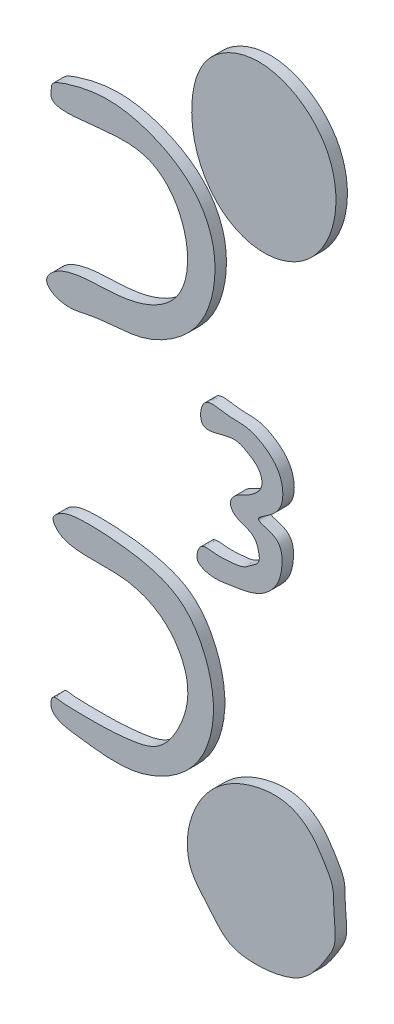
SolidWorks part; units mm, degrees
ref_plane "Plan de face" through (0, 0, 0) normal (0, 0, 1) x (1, 0, 0)
ref_plane "Plan de dessus" through (0, 0, 0) normal (0, 1, 0) x (1, 0, 0)
ref_plane "Plan de droite" through (0, 0, 0) normal (1, 0, 0) x (0, 0, -1)
sketch "Esquisse2" plane through (0, 0, 0) normal (0, 0, 1) x (1, 0, 0)
  spline S0 degree 3 poles (33.0398, 33.3108) (30.8437, 35.5747) (31.1487, 39.7884) (33.649, 43.2304) (37.0758, 44.68) (40.0093, 44.8048) (41.9924, 43.4542) (42.9933, 41.8752) (43.998, 40.2637) (43.802, 38.1648) (44.2434, 36.1904) (43.2504, 34.5258) (42.3581, 33.1589) (41.0307, 31.8624) (39.0658, 31.1858) (37.0142, 30.9623) (34.507, 31.3137) (33.0398, 33.3108) (30.8437, 35.5747) (31.1487, 39.7884) knots -0.170245 -0.123255 -0.059426 0 0.100099 0.211398 0.293708 0.362648 0.413623 0.458262 0.498625 0.546325 0.607041 0.636395 0.682371 0.726525 0.767054 0.829755 0.876745 0.940574 1 1.100099 1.211398 1.293708 only from (31.4862, 35.2825) to (31.4862, 35.2825)
  spline S1 degree 3 poles (32.2441, 97.9616) (31.205, 93.273) (31.9073, 89.3567) (33.8805, 86.3625) (37.3836, 84.8702) (41.5831, 85.9325) (44.5304, 90.388) (43.9096, 96.8861) (37.9571, 100.5086) (32.2441, 97.9616) (31.205, 93.273) (31.9073, 89.3567) knots -0.396579 -0.237542 -0.122038 0 0.076955 0.165433 0.247247 0.336953 0.456005 0.603421 0.762458 0.877962 1 1.076955 1.165433 1.247247 only from (31.4862, 92.6971) to (31.4862, 92.6971)
  spline S2 degree 3 poles (33.0432, 58.3081) (31.9134, 59.0241) (31.9311, 59.7097) (32.351, 60.568) (33.6185, 60.2941) (34.7915, 60.3881) (36.0182, 60.4842) (36.7184, 61.0966) (37.4833, 61.5586) (37.3384, 62.4873) (37.0146, 63.4183) (35.9976, 63.7876) (35.1127, 64.1142) (34.738, 64.9543) (35.2839, 65.7476) (36.153, 66.0752) (37.0241, 66.6082) (37.8092, 67.4844) (37.4074, 68.808) (36.3921, 69.4215) (34.8527, 70.2582) (31.986, 68.4617) (32.3579, 71.9659) (34.5883, 71.2479) (36.2703, 71.4438) (37.9414, 70.6474) (39.3618, 69.3261) (39.6137, 67.0468) (38.6303, 65.7785) (36.6531, 64.6995) (39.3775, 64.4209) (39.458, 62.4037) (39.0449, 60.6182) (37.4986, 59.0304) (35.0525, 58.6733) (33.0432, 58.3081) (31.9134, 59.0241) (31.9311, 59.7097) knots -0.116764 -0.062902 -0.006445 0 0.015981 0.029747 0.053635 0.082119 0.107798 0.124873 0.139963 0.15785 0.175957 0.198943 0.220104 0.23258 0.249661 0.271846 0.289785 0.313456 0.33757 0.363431 0.385064 0.446145 0.480391 0.519875 0.557582 0.58962 0.62952 0.67429 0.712535 0.736788 0.767963 0.811468 0.841391 0.883236 0.937098 0.993555 1 1.015981 1.029747 1.053635 only from (32.0774, 58.9558) to (32.0774, 58.9558)
  spline S3 degree 3 poles (22.9392, 40.3254) (18.9015, 40.9013) (19.2856, 42.5705) (20.2561, 42.3662) (21.6214, 42.3661) (23.6576, 42.3235) (25.9895, 42.4952) (28.6733, 42.9232) (30.5952, 45.6426) (31.6672, 49.4038) (29.5627, 53.2139) (25.5262, 54.8588) (22.2823, 54.3367) (19.9422, 54.8913) (19.116, 55.9998) (20.2334, 56.887) (22.0843, 57.1421) (24.7434, 56.9976) (27.7768, 56.5987) (30.8976, 55.3873) (33.0573, 51.9513) (33.7675, 47.4671) (31.8201, 42.6417) (26.7961, 39.8912) (22.9392, 40.3254) (18.9015, 40.9013) (19.2856, 42.5705) knots -0.191879 -0.116365 -0.037915 0 0.009718 0.016793 0.036826 0.072203 0.10212 0.139042 0.182965 0.235952 0.301061 0.347757 0.415504 0.438298 0.450012 0.464166 0.486698 0.533473 0.576157 0.619387 0.671802 0.742038 0.808121 0.883635 0.962085 1 1.009718 1.016793 1.036826 only from (19.1769, 41.8131) to (19.1769, 41.8131)
  spline S4 degree 3 poles (20.0967, 72.3565) (17.7666, 73.522) (20.1985, 75.171) (22.0752, 75.5677) (24.475, 75.5644) (27.4105, 75.9275) (30.5255, 77.8179) (31.5917, 81.9797) (29.9268, 86.305) (25.8539, 88.4091) (19.0378, 86.5191) (19.2204, 88.6304) (19.3063, 89.0076) (22.0943, 89.9903) (25.2388, 90.2349) (29.1823, 88.9616) (32.0924, 86.871) (33.4695, 83.8893) (33.6458, 80.2347) (32.1759, 76.1162) (26.8902, 72.8744) (24.4788, 73.3969) (20.0967, 72.3565) (17.7666, 73.522) (20.1985, 75.171) knots -0.200871 -0.071248 -0.051161 0 0.006359 0.018778 0.033086 0.053104 0.074272 0.09769 0.129043 0.152296 0.189987 0.195853 0.210958 0.24964 0.341579 0.412117 0.491572 0.550022 0.602635 0.709018 0.799129 0.928752 0.948839 1 1.006359 1.018778 1.033086 only from (19.37, 74.5843) to (19.37, 74.5843)
  point P118 (32.6809, 65)
extrude "Boss.-Extru.1" add sketch "Esquisse2" along normal blind 1
